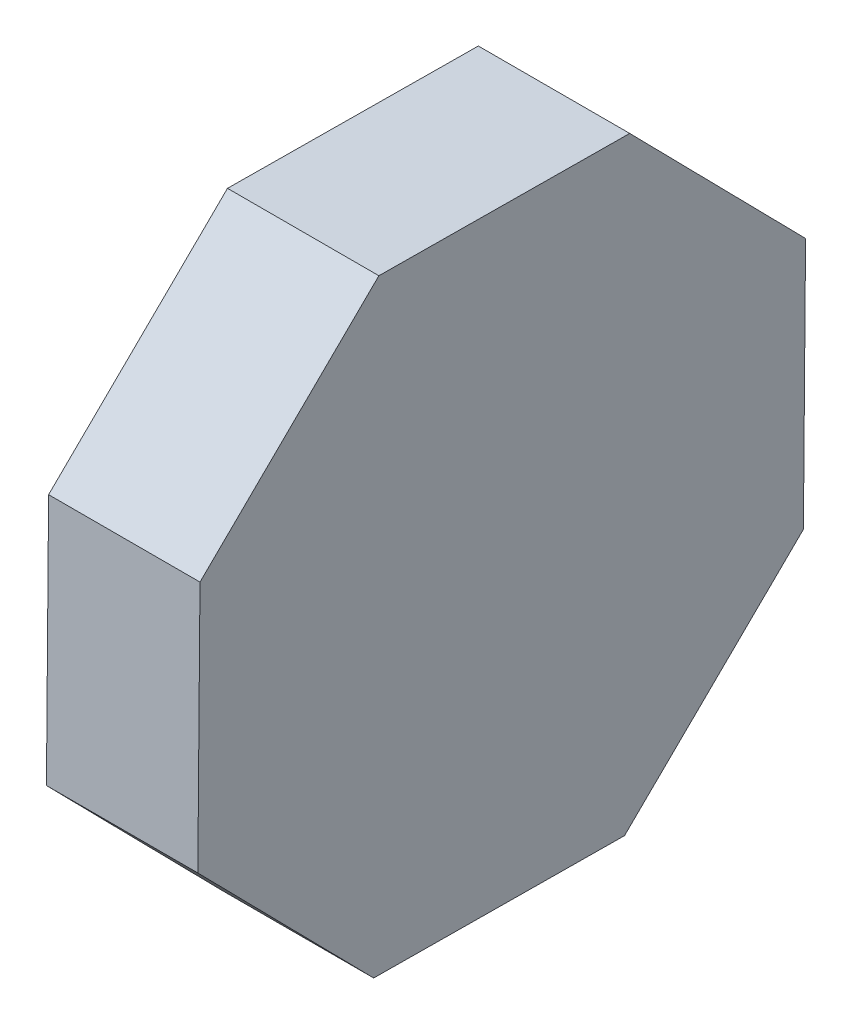
SolidWorks part; units mm, degrees
ref_plane "Front Plane" through (0, 0, 0) normal (0, 0, 1) x (1, 0, 0)
ref_plane "Top Plane" through (0, 0, 0) normal (0, 1, 0) x (1, 0, 0)
ref_plane "Right Plane" through (0, 0, 0) normal (1, 0, 0) x (0, 0, -1)
sketch "Sketch1" plane through (0, 0, 0) normal (1, 0, 0) x (0, 0, -1)
  line L1 (18.9813, -8.0546) -> (19.1173, 7.7264)
  line L2 (19.1173, 7.7264) -> (8.0546, 18.9813)
  line L3 (8.0546, 18.9813) -> (-7.7264, 19.1173)
  line L4 (-7.7264, 19.1173) -> (-18.9813, 8.0546)
  line L5 (-18.9813, 8.0546) -> (-19.1173, -7.7264)
  line L6 (-19.1173, -7.7264) -> (-8.0546, -18.9813)
  line L7 (-8.0546, -18.9813) -> (7.7264, -19.1173)
  line L8 (7.7264, -19.1173) -> (18.9813, -8.0546)
  circle A0 centre (0, 0) radius 19.05 construction
  dimension "D1" = 38.1
extrude "Boss-Extrude1" add sketch "Sketch1" along normal blind 9.525
sketch "Sketch2" plane through (0, 0, 0) normal (-1, 0, 0) x (0, 0, 1)
  circle A0 centre (0, 0) radius 4.2355
  dimension "D1" = 8.4709
extrude "Cut-Extrude1" cut sketch "Sketch2" against normal blind 4.7625
